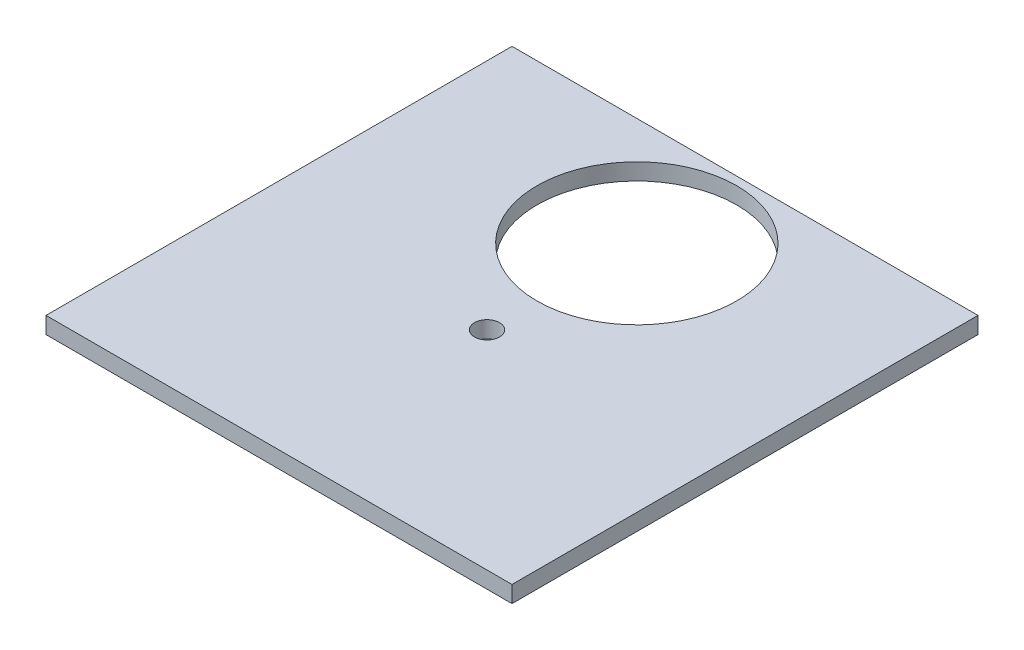
SolidWorks part; units mm, degrees
ref_plane "Front Plane" through (0, 0, 0) normal (0, 0, 1) x (1, 0, 0)
ref_plane "Top Plane" through (0, 0, 0) normal (0, 1, 0) x (1, 0, 0)
ref_plane "Right Plane" through (0, 0, 0) normal (1, 0, 0) x (0, 0, -1)
sketch "Sketch1" plane through (0, 0, 0) normal (0, 1, 0) x (1, 0, 0)
  line L1 (-25.4131, -30.9036) -> (45.7069, -30.9036)
  line L2 (-25.4131, -30.9036) -> (-25.4131, 40.2164)
  line L3 (-25.4131, 40.2164) -> (45.7069, 40.2164)
  line L4 (45.7069, -30.9036) -> (45.7069, 40.2164)
  point P0 (0, 0)
extrude "Boss-Extrude1" add sketch "Sketch1" against normal blind 2.54
sketch "Sketch2" plane through (0, 0, 0) normal (0, 1, 0) x (1, 0, 0)
  circle A0 centre (10.1469, 23.7064) radius 15.24
extrude "Cut-Extrude1" cut sketch "Sketch2" against normal blind 15.748
sketch "Sketch4" plane through (0, 0, 0) normal (0, 1, 0) x (1, 0, 0)
  circle A0 centre (10.1469, 0.8464) radius 1.905
  point P0 (0, 0)
extrude "Cut-Extrude2" cut sketch "Sketch4" against normal blind 15.748
